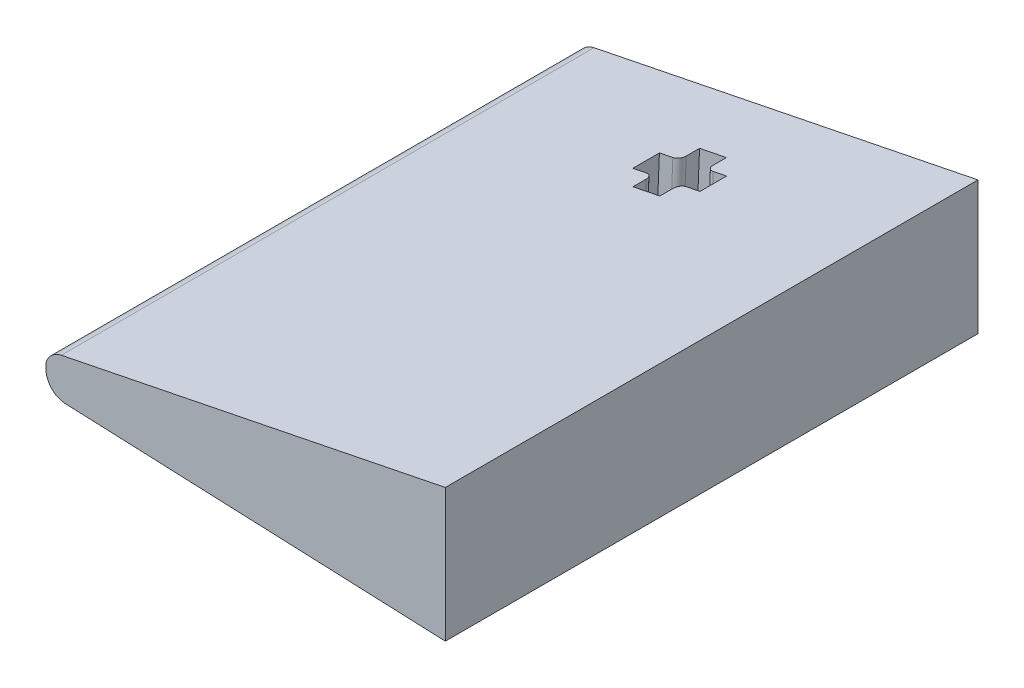
SolidWorks part; units mm, degrees
ref_plane "Front Plane" through (0, 0, 0) normal (0, 0, 1) x (1, 0, 0)
ref_plane "Top Plane" through (0, 0, 0) normal (0, 1, 0) x (1, 0, 0)
ref_plane "Right Plane" through (0, 0, 0) normal (1, 0, 0) x (0, 0, -1)
sketch "Sketch1" plane through (0, 0, 0) normal (0, 0, 1) x (1, 0, 0)
  line L1 (30.0477, 0) -> (30.0477, 5.3586)
  line L2 (30.0477, 0) -> (30.0477, -4.6414)
  line L4 (0.0627, -1.5125) -> (0.0627, -1.9458)
  line L5 (1.215, -0.4591) -> (30.0477, 5.3586)
  line L6 (1.5146, -3.4591) -> (30.0477, -4.6414)
  arc A0 (1.5146, -3.4591) -> (0.0627, -1.9458) centre (1.5773, -1.9458) cw
  arc A1 (0.0627, -1.5125) -> (1.215, -0.4591) centre (1.5146, -1.9438) cw
  point P11 (0, 0)
  point P12 (0, 0)
  point P13 (0, 0)
  point P14 (1.5146, -3.0564)
  point P15 (0, 0)
  point P16 (30.0477, -4.3944)
  point P17 (30.0477, -3.0639)
  point P18 (1.215, -0.4591)
  point P19 (0, 0)
  point P20 (0, 0)
  point P21 (0, 0)
  point P22 (0, 0)
  point P23 (0, 0)
  point P24 (0.0002, -1.9205)
  dimension "D1" = 1.5146
  dimension "D2" = 10
  dimension "D3" = 3
extrude "Boss-Extrude1" add sketch "Sketch1" along normal blind 40
sketch "Sketch3" plane through (-0.1405, -3.3905, 0) normal (-0.0414, -0.9991, 0) x (0.9991, -0.0414, 0)
  line L0 (15.9353, 80) -> (15.9353, 0) construction
  line L4 (1.6565, 0) -> (30.2141, 0) construction
  point P3 (15.9353, 40)
sketch "Sketch5" plane through (-0.1405, -3.3905, 0) normal (-0.0414, -0.9991, 0) x (0.9991, -0.0414, 0)
  line L3 (17.7738, 7.7386) -> (17.7738, 8.7386)
  line L7 (12.7738, 8.7386) -> (12.7738, 6.7386)
  line L9 (17.7738, 8.7386) -> (16.7738, 8.7386)
  line L10 (17.7738, 7.7386) -> (17.7738, 6.7386)
  line L11 (14.2738, 6.2386) -> (14.2738, 5.2386)
  line L12 (15.2738, 5.2386) -> (14.2738, 5.2386)
  line L13 (15.2738, 5.2386) -> (16.2738, 5.2386)
  line L14 (16.2738, 9.2386) -> (16.2738, 10.2386)
  line L15 (16.2738, 10.2386) -> (14.2738, 10.2386)
  line L16 (14.2738, 10.2386) -> (14.2738, 9.2386)
  line L17 (17.7738, 8.7386) -> (16.7738, 8.7386)
  line L18 (16.2738, 9.2386) -> (16.2738, 10.2386)
  line L19 (14.2738, 10.2386) -> (14.2738, 9.2386)
  line L20 (13.7738, 8.7386) -> (12.7738, 8.7386)
  line L21 (12.7738, 6.7386) -> (13.7738, 6.7386)
  line L22 (14.2738, 6.2386) -> (14.2738, 5.2386)
  line L23 (16.2738, 5.2386) -> (16.2738, 6.2386)
  line L24 (16.7738, 6.7386) -> (17.7738, 6.7386)
  arc A0 (16.7738, 8.7386) -> (16.2738, 9.2386) centre (16.7738, 9.2386) cw
  arc A1 (14.2738, 9.2386) -> (13.7738, 8.7386) centre (13.7738, 9.2386) cw
  arc A2 (13.7738, 6.7386) -> (14.2738, 6.2386) centre (13.7738, 6.2386) cw
  arc A3 (16.2738, 6.2386) -> (16.7738, 6.7386) centre (16.7738, 6.2386) cw
  point P6 (14.2738, 8.7386)
  point P25 (14.2738, 6.7386)
  point P28 (16.2738, 6.7386)
  dimension "D1" = 0.5
  dimension "D2" = 0.5
extrude "Cut-Extrude1" cut sketch "Sketch5" against normal blind 239 contours L23 A3 L24 L10 L3 L9 A0 L14 L15 L16 A1 L20 L7 L21 A2 L11 L12 L13
